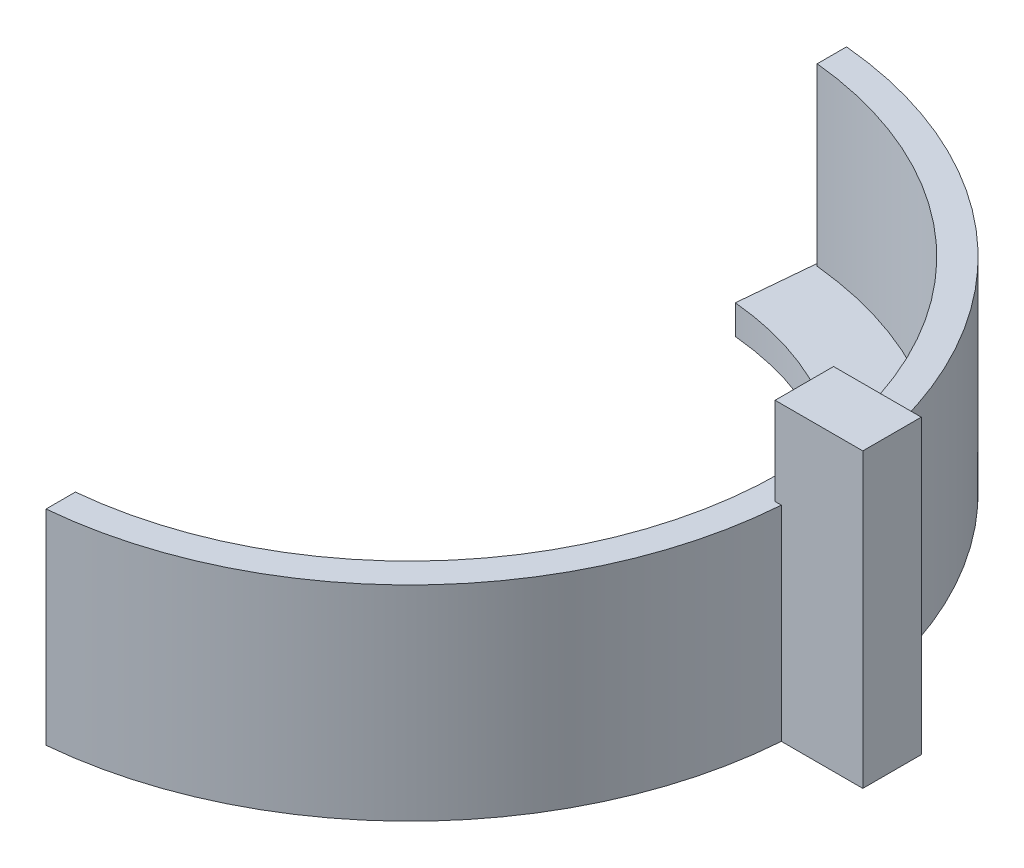
SolidWorks part; units mm, degrees
ref_plane "Front Plane" through (0, 0, 0) normal (0, 0, 1) x (1, 0, 0)
ref_plane "Top Plane" through (0, 0, 0) normal (0, 1, 0) x (1, 0, 0)
ref_plane "Right Plane" through (0, 0, 0) normal (1, 0, 0) x (0, 0, -1)
sketch "Sketch1" plane through (0, 0, 0) normal (0, 1, 0) x (1, 0, 0)
  line L4 (2.5, 27.3861) -> (2.5, 25.3772)
  line L6 (-2.5, 0) -> (2.5, 0) construction
  line L7 (2.5, -25.3772) -> (2.5, -27.3861)
  arc A2 (2.5, -27.3861) -> (2.5, 27.3861) centre (0, 0) ccw
  arc A5 (2.5, -25.3772) -> (2.5, 25.3772) centre (0, 0) ccw
  point P4 (24.3858, 7.4555)
  point P12 (26.2984, 8.0402)
extrude "Boss-Extrude1" add sketch "Sketch1" along normal blind 12
sketch "Sketch2" plane through (0, 0, 0) normal (0, 1, 0) x (1, 0, 0)
  line L0 (2.5, 27.3861) -> (1.8636, 20.4151)
  line L1 (2.5, -27.3861) -> (1.8636, -20.4151)
  arc A0 (2.5, 27.3861) -> (2.5, -27.3861) centre (0, 0) cw
  arc A1 (1.8636, 20.4151) -> (1.8636, -20.4151) centre (0, 0) cw
  dimension "D1" = 7
extrude "Boss-Extrude2" add sketch "Sketch2" against normal blind 2
sketch "Sketch4" plane through (0, -2, 0) normal (0, 1, 0) x (1, 0, 0)
  line L1 (27, 2) -> (33, 2)
  line L2 (27, 2) -> (27, -2)
  line L3 (27, -2) -> (33, -2)
  line L4 (33, 2) -> (33, -2)
  line L5 (30, -2) -> (30, 2) construction
  line L6 (27, 0) -> (33, 0) construction
  point P0 (30, 0)
  point P4 (0, 0)
  dimension "D1" = 6
  dimension "D2" = 4
  dimension "D3" = 30
extrude "Boss-Extrude3" add sketch "Sketch4" along normal blind 20
